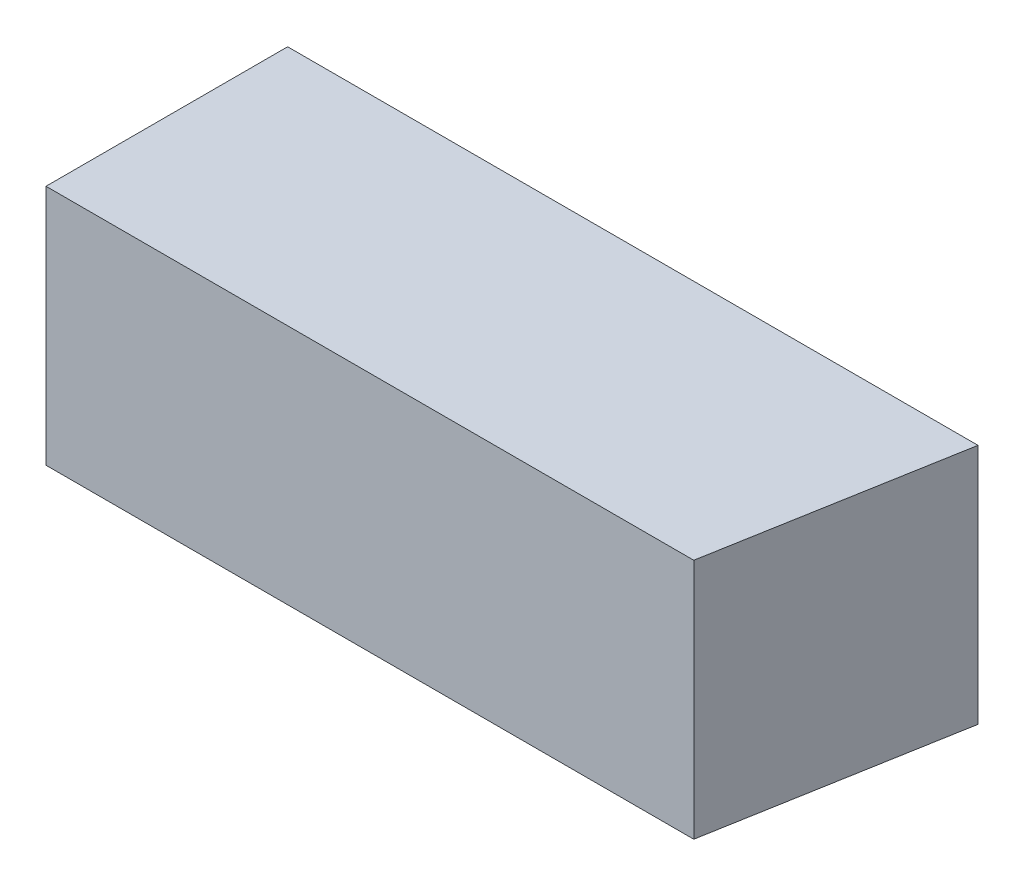
SolidWorks part; units mm, degrees
ref_plane "Front Plane" through (0, 0, 0) normal (1, 0, 0) x (0, 1, 0)
ref_plane "Top Plane" through (0, 0, 0) normal (0, 0, 1) x (0, 1, 0)
ref_plane "Right Plane" through (0, 0, 0) normal (0, 1, 0) x (-1, 0, 0)
sketch "Sketch1" plane through (0, 0, 0) normal (1, 0, 0) x (0, 1, 0)
  line L1 (0, 0) -> (88.9, 0)
  line L2 (0, 0) -> (0, 88.9)
  line L3 (0, 88.9) -> (88.9, 88.9)
  line L4 (88.9, 0) -> (88.9, 88.9)
  dimension "D1" = 88.9
  dimension "D2" = 88.9
extrude "Boss-Extrude1" add sketch "Sketch1" along normal blind 254
sketch "Sketch2" plane through (0, 0, 0) normal (0, 1, 0) x (-1, 0, 0)
  line L0 (-254, 0) -> (-238.3269, 88.9)
  line L1 (-254, 88.9) -> (0, 88.9) construction
  line L2 (-238.3269, 88.9) -> (-254, 88.9)
  line L3 (-254, 88.9) -> (-254, 0)
  dimension "D1" = 15.6731
extrude "Cut-Extrude1" cut sketch "Sketch2" along normal blind 88.9
